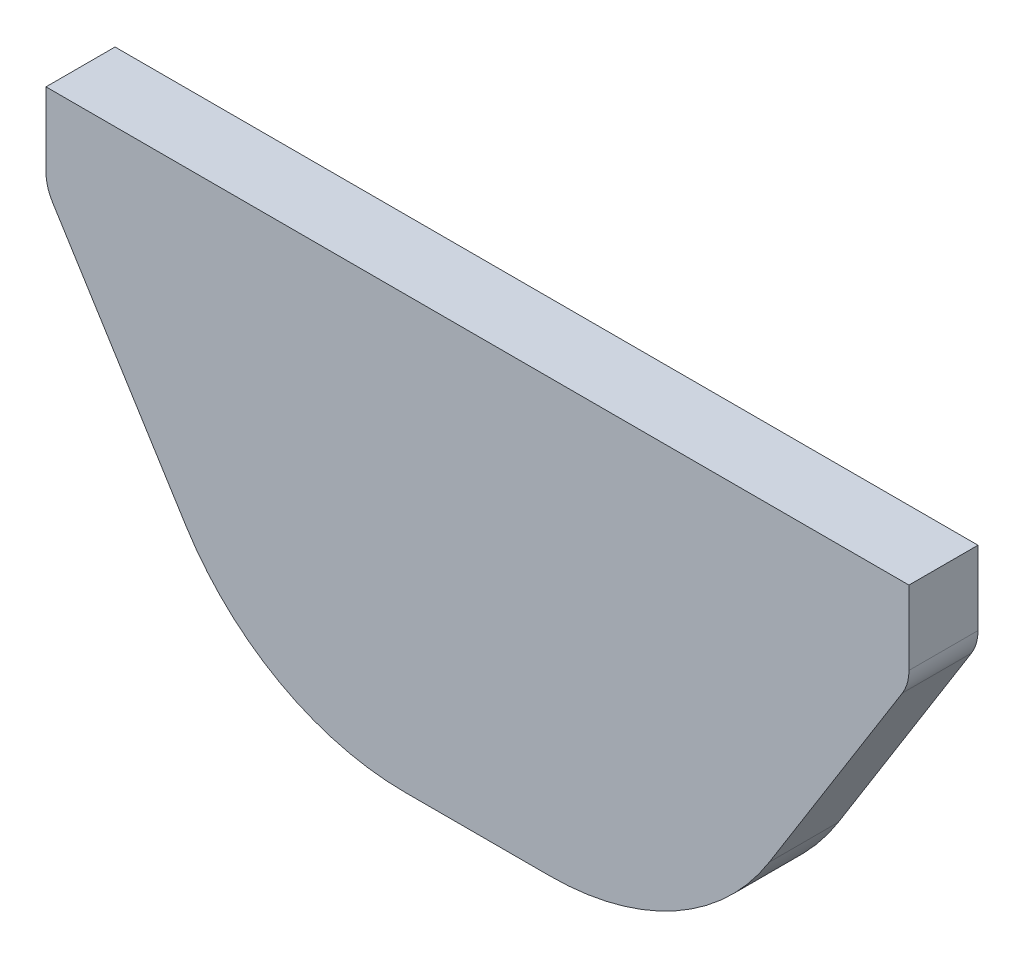
SolidWorks part; units mm, degrees
material "Q355"
ref_plane "前视基准面" through (0, 0, 0) normal (0, 0, 1) x (1, 0, 0)
ref_plane "上视基准面" through (0, 0, 0) normal (0, 1, 0) x (1, 0, 0)
ref_plane "右视基准面" through (0, 0, 0) normal (1, 0, 0) x (0, 0, -1)
sketch "草图1" plane through (0, 0, 0) normal (0, 0, 1) x (1, 0, 0)
  line L0 (0, 0) -> (0, 63.8973) construction
  line L1 (-25, 0) -> (25, 0)
  line L2 (25, 0) -> (50, 40)
  line L3 (50, 40) -> (50, 50)
  line L4 (50, 50) -> (-50, 50)
  line L5 (-50, 40) -> (-50, 50)
  line L6 (-25, 0) -> (-50, 40)
  point P8 (0, 50)
  dimension "D1" = 50
  dimension "D2" = 10
  dimension "D3" = 100
  dimension "D4" = 50
extrude "凸台-拉伸1" add sketch "草图1" along normal blind 8
fillet "圆角1" radius 30 2 edges at (-25, 0, 4) (25, 0, 4)
fillet "圆角2" radius 5 2 edges at (-50, 40, 4) (50, 40, 4)
